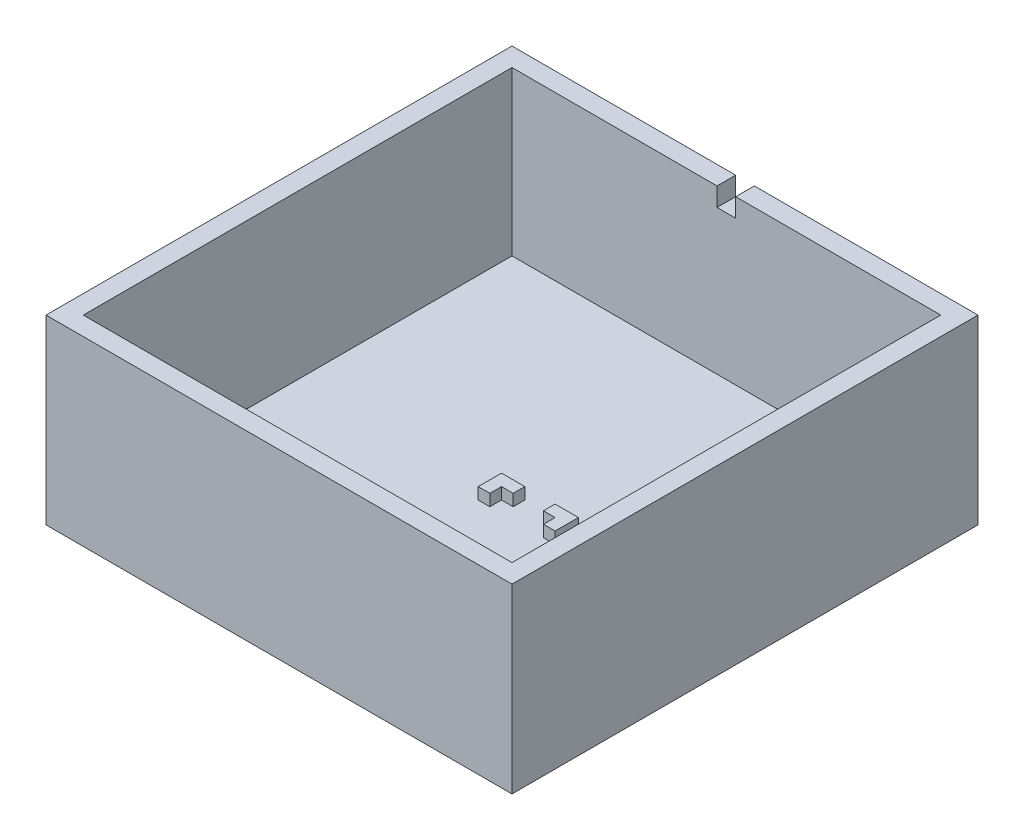
SolidWorks part; units mm, degrees
ref_plane "Front Plane" through (0, 0, 0) normal (0, 0, 1) x (1, 0, 0)
ref_plane "Top Plane" through (0, 0, 0) normal (0, 1, 0) x (1, 0, 0)
ref_plane "Right Plane" through (0, 0, 0) normal (1, 0, 0) x (0, 0, -1)
sketch "Sketch1" plane through (0, 0, 0) normal (0, 1, 0) x (1, 0, 0)
  line L1 (-50, -50) -> (50, -50)
  line L2 (-50, -50) -> (-50, 50)
  line L3 (-50, 50) -> (50, 50)
  line L4 (50, -50) -> (50, 50)
  line L5 (-50, -50) -> (50, 50) construction
  line L6 (-50, 50) -> (50, -50) construction
  point P0 (0, 0)
  dimension "D1" = 100
extrude "Boss-Extrude1" add sketch "Sketch1" along normal blind 4
sketch "Sketch2" plane through (0, 4, 0) normal (0, 1, 0) x (1, 0, 0)
  line L0 (46, -46) -> (46, 46)
  line L1 (46, 46) -> (-46, 46)
  line L2 (-46, 46) -> (-46, -46)
  line L3 (-46, -46) -> (46, -46)
  line L4 (50, -50) -> (50, 50)
  line L5 (50, 50) -> (-50, 50)
  line L6 (-50, 50) -> (-50, -50)
  line L7 (-50, -50) -> (50, -50)
  line L8 (50, -50) -> (50, 50)
  line L9 (50, 50) -> (-50, 50)
  line L10 (-50, 50) -> (-50, -50)
  line L11 (-50, -50) -> (50, -50)
  dimension "D1" = 0
  dimension "D2" = 4
extrude "Boss-Extrude2" add sketch "Sketch2" along normal blind 35
sketch "Sketch3" plane through (0, 0, -50) normal (0, 0, -1) x (-1, 0, 0)
  line L0 (-50, 39) -> (50, 39) construction
  line L1 (2, 35) -> (-2, 35)
  line L2 (2, 35) -> (2, 39)
  line L3 (2, 39) -> (-2, 39)
  line L4 (-2, 35) -> (-2, 39)
  line L5 (2, 35) -> (-2, 39) construction
  line L6 (2, 39) -> (-2, 35) construction
  point P0 (0, 37)
  point P7 (0, 0)
  dimension "D1" = 4
extrude "Cut-Extrude1" cut sketch "Sketch3" against normal up to surface (4 mm away) up to face at (0, 21.5, -46)
sketch "Sketch4" plane through (0, 4, 0) normal (0, 1, 0) x (1, 0, 0)
  line L1 (9.75, -0.5) -> (-1.75, -0.5)
  line L2 (9.75, -0.5) -> (9.75, -17)
  line L3 (9.75, -17) -> (-1.75, -17)
  line L4 (-1.75, -0.5) -> (-1.75, -17)
  line L5 (9.75, -0.5) -> (-1.75, -17) construction
  line L6 (9.75, -17) -> (-1.75, -0.5) construction
  line L7 (14, 19) -> (-6, 19)
  line L8 (14, 19) -> (14, -21)
  line L9 (14, -21) -> (-6, -21)
  line L10 (-6, 19) -> (-6, -21)
  line L11 (14, 19) -> (-6, -21) construction
  line L12 (14, -21) -> (-6, 19) construction
  line L17 (-46, -46) -> (46, -46) construction
  line L26 (46, -46) -> (46, 46) construction
  line L28 (12.25, -19.5) -> (7.25, -19.5)
  line L29 (12.25, -19.5) -> (12.25, -14.5)
  line L30 (12.25, -14.5) -> (7.25, -14.5)
  line L31 (7.25, -19.5) -> (7.25, -14.5)
  line L32 (12.25, -19.5) -> (7.25, -14.5) construction
  line L33 (12.25, -14.5) -> (7.25, -19.5) construction
  line L34 (-4.25, -19.5) -> (0.75, -19.5)
  line L35 (-4.25, -19.5) -> (-4.25, -14.5)
  line L36 (-4.25, -14.5) -> (0.75, -14.5)
  line L37 (0.75, -19.5) -> (0.75, -14.5)
  line L38 (-4.25, -19.5) -> (0.75, -14.5) construction
  line L39 (-4.25, -14.5) -> (0.75, -19.5) construction
  line L40 (12.25, 2) -> (7.25, 2)
  line L41 (12.25, 2) -> (12.25, -3)
  line L42 (12.25, -3) -> (7.25, -3)
  line L43 (7.25, 2) -> (7.25, -3)
  line L44 (12.25, 2) -> (7.25, -3) construction
  line L45 (12.25, -3) -> (7.25, 2) construction
  line L46 (-4.25, 2) -> (0.75, 2)
  line L47 (-4.25, 2) -> (-4.25, -3)
  line L48 (-4.25, -3) -> (0.75, -3)
  line L49 (0.75, 2) -> (0.75, -3)
  line L50 (-4.25, 2) -> (0.75, -3) construction
  line L51 (-4.25, -3) -> (0.75, 2) construction
  point P0 (4, -8.75)
  point P5 (4, -1)
  dimension "D1" = 11.5
  dimension "D2" = 16.5
  dimension "D3" = 32
  dimension "D4" = 25
  dimension "D5" = 40
  dimension "D6" = 20
  dimension "D7" = 4
  dimension "D8" = 2.5
  dimension "D9" = 2.5
extrude "Boss-Extrude3" add sketch "Sketch4" along normal blind 2.5 contours L49 L46 L47 L48 L4 L1 | L40 L43 L1 L2 L42 L41 | L31 L28 L29 L30 L2 L3 | L34 L37 L3 L4 L36 L35
sketch "Sketch5" plane through (0, 4, 0) normal (0, 1, 0) x (1, 0, 0)
  line L1 (4, -13) -> (-1.75, -13)
  line L2 (4, -13) -> (4, -17)
  line L3 (4, -17) -> (-1.75, -17)
  line L4 (-1.75, -13) -> (-1.75, -17)
  line L5 (4, -13) -> (-1.75, -17) construction
  line L6 (4, -17) -> (-1.75, -13) construction
  point P0 (1.125, -15)
  point P6 (5.3258, -12.3502)
  dimension "D1" = 4
  dimension "D2" = 5.75
extrude "Cut-Extrude2" cut sketch "Sketch5" against normal up to surface (4 mm away) up to face at (0, 0, 0)
